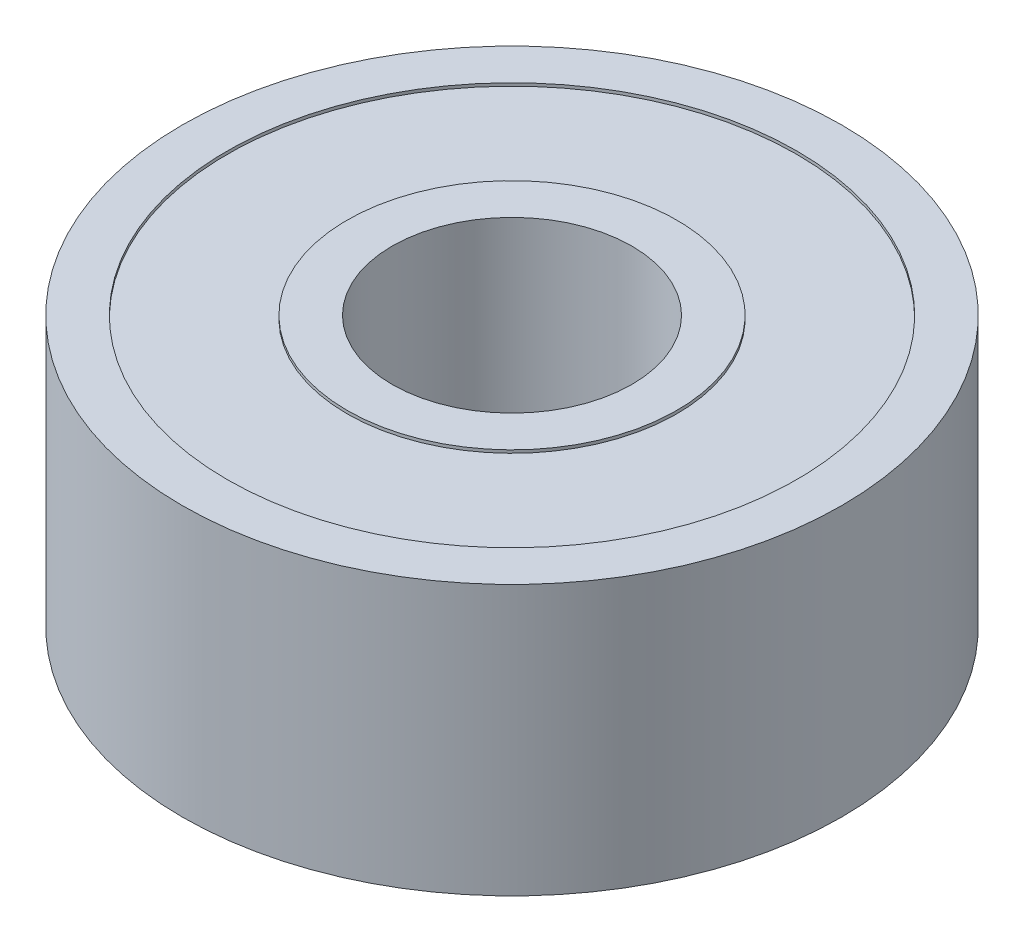
SolidWorks part; units mm, degrees
ref_plane "Front Plane" through (0, 0, 0) normal (0, 0, 1) x (1, 0, 0)
ref_plane "Top Plane" through (0, 0, 0) normal (0, 1, 0) x (1, 0, 0)
ref_plane "Right Plane" through (0, 0, 0) normal (1, 0, 0) x (0, 0, -1)
sketch "Sketch1" plane through (0, 0, 0) normal (0, 1, 0) x (1, 0, 0)
  circle A0 centre (0, 0) radius 4
  circle A1 centre (0, 0) radius 11
  dimension "D1" = 8
  dimension "D2" = 22
extrude "Boss-Extrude1" add sketch "Sketch1" along normal blind 9
sketch "Sketch2" plane through (0, 9, 0) normal (0, 1, 0) x (1, 0, 0)
  circle A0 centre (0, 0) radius 5.5
  circle A1 centre (0, 0) radius 9.5
  circle A2 centre (0, 0) radius 11 construction
  circle A3 centre (0, 0) radius 4 construction
  dimension "D1" = 1.5
  dimension "D2" = 1.5
extrude "Cut-Extrude1" cut sketch "Sketch2" against normal blind 0.1
sketch "Sketch3" plane through (0, 0, 0) normal (0, -1, 0) x (1, 0, 0)
  circle A0 centre (0, 0) radius 5.5 construction
  circle A1 centre (0, 0) radius 9.5
  circle A2 centre (0, 0) radius 9.5
  circle A3 centre (0, 0) radius 5.5
  dimension "D1" = 0
extrude "Cut-Extrude2" cut sketch "Sketch3" against normal blind 0.1
equation "\"D2@Sketch2\"=\"D1@Sketch2\""
